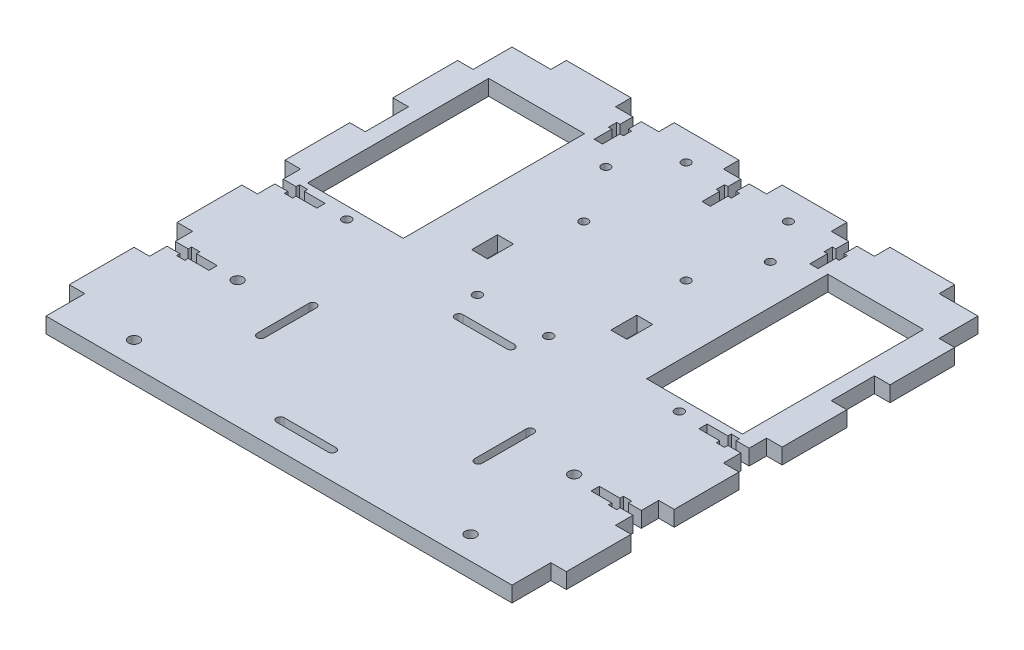
SolidWorks part; units mm, degrees
material "Oak"
ref_plane "Front Plane" through (0, 0, 0) normal (0, 0, 1) x (1, 0, 0)
ref_plane "Top Plane" through (0, 0, 0) normal (0, 1, 0) x (1, 0, 0)
ref_plane "Right Plane" through (0, 0, 0) normal (1, 0, 0) x (0, 0, -1)
sketch "Sketch1" plane through (0, 0, 0) normal (0, 1, 0) x (1, 0, 0)
  line L0 (0, -3.3) -> (0, 3.3) construction
  line L1 (-90, -90) -> (90, -90)
  line L2 (-90, -90) -> (-90, -75)
  line L3 (-90, 90) -> (-75, 90)
  line L4 (90, -90) -> (90, -75)
  line L5 (-90, -90) -> (90, 90) construction
  line L6 (-90, 90) -> (90, -90) construction
  line L7 (23.8, 24.4) -> (30, 24.4)
  line L8 (23.8, 24.4) -> (23.8, 14.4)
  line L9 (23.8, 14.4) -> (30, 14.4)
  line L10 (30, 24.4) -> (30, 14.4)
  line L11 (47, 75) -> (84, 75)
  line L12 (47, 75) -> (47, 5)
  line L13 (47, 5) -> (84, 5)
  line L14 (84, 75) -> (84, 5)
  line L15 (-47, 5) -> (-84, 5)
  line L16 (-84, 75) -> (-84, 5)
  line L17 (-47, 75) -> (-84, 75)
  line L18 (-47, 75) -> (-47, 5)
  line L19 (-23.8, 14.4) -> (-30, 14.4)
  line L20 (-30, 24.4) -> (-30, 14.4)
  line L21 (-23.8, 24.4) -> (-30, 24.4)
  line L22 (-23.8, 24.4) -> (-23.8, 14.4)
  line L24 (30, 19.4) -> (47, 19.4) construction
  line L25 (-90, 75) -> (-96, 75)
  line L27 (-90, 50) -> (-96, 50)
  line L28 (-96, 75) -> (-96, 50)
  line L29 (-90, 33.3333) -> (-96, 33.3333)
  line L30 (-96, 33.3333) -> (-96, 8.3333)
  line L31 (-90, 8.3333) -> (-96, 8.3333)
  line L33 (-90, -8.3333) -> (-96, -8.3333)
  line L34 (-96, -8.3333) -> (-96, -33.3333)
  line L35 (-90, -33.3333) -> (-96, -33.3333)
  line L37 (-90, -50) -> (-96, -50)
  line L38 (-96, -50) -> (-96, -75)
  line L39 (-90, -75) -> (-96, -75)
  line L40 (-90, 33.3333) -> (-90, 50)
  line L41 (-90, 1.6) -> (-85, 1.6)
  line L43 (-90, -1.6) -> (-85, -1.6)
  line L44 (-73.8, 1.6) -> (-73.8, -1.6)
  line L45 (-85, 2.9) -> (-81.8, 2.9)
  line L46 (-85, 2.9) -> (-85, 1.6)
  line L47 (-85, -2.9) -> (-81.8, -2.9)
  line L48 (-81.8, 2.9) -> (-81.8, 1.6)
  line L49 (-42, -35) -> (-42, -55) construction
  line L50 (-90, 75) -> (-90, 90)
  line L51 (-90, -8.3333) -> (-90, -1.6)
  line L52 (-90, -50) -> (-90, -43.2667)
  line L53 (-85, -1.6) -> (-85, -2.9)
  line L54 (-81.8, -1.6) -> (-73.8, -1.6)
  line L55 (-81.8, 1.6) -> (-73.8, 1.6)
  line L56 (-81.8, -1.6) -> (-81.8, -2.9)
  line L57 (-90, 1.6) -> (-90, 8.3333)
  line L58 (-90, -40.0667) -> (-85, -40.0667)
  line L59 (-90, -43.2667) -> (-85, -43.2667)
  line L60 (-73.8, -40.0667) -> (-73.8, -43.2667)
  line L61 (-85, -38.7667) -> (-81.8, -38.7667)
  line L62 (-85, -38.7667) -> (-85, -40.0667)
  line L63 (-85, -44.5667) -> (-81.8, -44.5667)
  line L64 (-81.8, -38.7667) -> (-81.8, -40.0667)
  line L65 (-85, -43.2667) -> (-85, -44.5667)
  line L66 (-81.8, -43.2667) -> (-73.8, -43.2667)
  line L67 (-81.8, -40.0667) -> (-73.8, -40.0667)
  line L68 (-81.8, -43.2667) -> (-81.8, -44.5667)
  line L69 (-90, -40.0667) -> (-90, -33.3333)
  line L70 (90, -75) -> (96, -75)
  line L71 (81.8, -38.7667) -> (81.8, -40.0667)
  line L72 (85, -38.7667) -> (81.8, -38.7667)
  line L73 (85, -38.7667) -> (85, -40.0667)
  line L74 (81.8, -43.2667) -> (81.8, -44.5667)
  line L75 (81.8, -40.0667) -> (73.8, -40.0667)
  line L76 (81.8, -43.2667) -> (73.8, -43.2667)
  line L77 (85, -43.2667) -> (85, -44.5667)
  line L78 (85, -44.5667) -> (81.8, -44.5667)
  line L79 (73.8, -40.0667) -> (73.8, -43.2667)
  line L80 (90, -43.2667) -> (85, -43.2667)
  line L81 (90, -40.0667) -> (85, -40.0667)
  line L82 (96, -50) -> (96, -75)
  line L83 (90, -50) -> (96, -50)
  line L84 (90, -33.3333) -> (96, -33.3333)
  line L85 (90, -8.3333) -> (96, -8.3333)
  line L86 (96, -8.3333) -> (96, -33.3333)
  line L87 (81.8, -1.6) -> (81.8, -2.9)
  line L88 (81.8, 1.6) -> (73.8, 1.6)
  line L89 (81.8, -1.6) -> (73.8, -1.6)
  line L90 (85, -1.6) -> (85, -2.9)
  line L91 (81.8, 2.9) -> (81.8, 1.6)
  line L92 (85, -2.9) -> (81.8, -2.9)
  line L93 (85, 2.9) -> (85, 1.6)
  line L94 (85, 2.9) -> (81.8, 2.9)
  line L95 (73.8, 1.6) -> (73.8, -1.6)
  line L96 (90, -1.6) -> (85, -1.6)
  line L97 (90, 1.6) -> (85, 1.6)
  line L98 (90, 8.3333) -> (96, 8.3333)
  line L99 (96, 33.3333) -> (96, 8.3333)
  line L100 (90, 33.3333) -> (96, 33.3333)
  line L101 (90, 50) -> (96, 50)
  line L102 (96, 75) -> (96, 50)
  line L103 (90, 75) -> (96, 75)
  line L104 (90, 75) -> (90, 90)
  line L105 (90, 33.3333) -> (90, 50)
  line L106 (90, 1.6) -> (90, 8.3333)
  line L107 (90, -8.3333) -> (90, -1.6)
  line L108 (90, -50) -> (90, -43.2667)
  line L109 (90, -40.0667) -> (90, -33.3333)
  line L110 (-33.3333, 90) -> (-33.3333, 96)
  line L112 (-75, 90) -> (-75, 96)
  line L113 (-75, 96) -> (-50, 96)
  line L114 (-50, 90) -> (-50, 96)
  line L116 (-8.3333, 90) -> (-8.3333, 96)
  line L117 (-33.3333, 96) -> (-8.3333, 96)
  line L118 (8.3333, 90) -> (8.3333, 96)
  line L120 (33.3333, 90) -> (33.3333, 96)
  line L121 (8.3333, 96) -> (33.3333, 96)
  line L122 (50, 90) -> (50, 96)
  line L124 (75, 90) -> (75, 96)
  line L125 (50, 96) -> (75, 96)
  line L126 (-40.0667, 90) -> (-33.3333, 90)
  line L128 (-43.2667, 90) -> (-43.2667, 85)
  line L129 (-43.2667, 75) -> (-40.0667, 75)
  line L130 (-40.0667, 90) -> (-40.0667, 85)
  line L131 (-50, 90) -> (-43.2667, 90)
  line L132 (-8.3333, 90) -> (-1.6, 90)
  line L133 (-40.0667, 85) -> (-38.7667, 85)
  line L134 (-44.5667, 85) -> (-43.2667, 85)
  line L135 (-44.5667, 85) -> (-44.5667, 81.8)
  line L136 (-44.5667, 81.8) -> (-43.2667, 81.8)
  line L137 (-38.7667, 85) -> (-38.7667, 81.8)
  line L138 (-43.2667, 81.8) -> (-43.2667, 75)
  line L139 (-40.0667, 81.8) -> (-38.7667, 81.8)
  line L140 (-40.0667, 81.8) -> (-40.0667, 75)
  line L141 (-1.6, 90) -> (-1.6, 85)
  line L142 (-1.6, 75) -> (1.6, 75)
  line L143 (1.6, 90) -> (1.6, 85)
  line L144 (1.6, 85) -> (2.9, 85)
  line L145 (-2.9, 85) -> (-1.6, 85)
  line L146 (-2.9, 85) -> (-2.9, 81.8)
  line L147 (-2.9, 81.8) -> (-1.6, 81.8)
  line L148 (2.9, 85) -> (2.9, 81.8)
  line L149 (-1.6, 81.8) -> (-1.6, 75)
  line L150 (1.6, 81.8) -> (2.9, 81.8)
  line L151 (1.6, 81.8) -> (1.6, 75)
  line L152 (40.0667, 90) -> (40.0667, 85)
  line L153 (40.0667, 75) -> (43.2667, 75)
  line L154 (43.2667, 90) -> (43.2667, 85)
  line L155 (43.2667, 85) -> (44.5667, 85)
  line L156 (38.7667, 85) -> (40.0667, 85)
  line L157 (38.7667, 85) -> (38.7667, 81.8)
  line L158 (38.7667, 81.8) -> (40.0667, 81.8)
  line L159 (44.5667, 85) -> (44.5667, 81.8)
  line L160 (40.0667, 81.8) -> (40.0667, 75)
  line L161 (43.2667, 81.8) -> (44.5667, 81.8)
  line L162 (43.2667, 81.8) -> (43.2667, 75)
  line L163 (1.6, 90) -> (8.3333, 90)
  line L164 (43.2667, 90) -> (50, 90)
  line L165 (33.3333, 90) -> (40.0667, 90)
  line L166 (75, 90) -> (90, 90)
  line L167 (-40.5, -35) -> (-40.5, -55)
  line L168 (-43.5, -35) -> (-43.5, -55)
  line L169 (-90, -75) -> (-90, -50) construction
  line L170 (42, -35) -> (42, -55) construction
  line L171 (40.5, -35) -> (40.5, -55)
  line L172 (43.5, -35) -> (43.5, -55)
  line L173 (10, -10.5) -> (-10, -10.5) construction
  line L174 (10, -12) -> (-10, -12)
  line L175 (10, -9) -> (-10, -9)
  line L176 (-42, -45) -> (42, -45) construction
  line L177 (10, -79.5) -> (-10, -79.5) construction
  line L178 (10, -78) -> (-10, -78)
  line L179 (10, -81) -> (-10, -81)
  circle A0 centre (65, -41) radius 2.1
  circle A1 centre (65, -81) radius 2.1
  circle A3 centre (-65, -81) radius 2.1
  circle A5 centre (-65, -41) radius 2.1
  circle A6 centre (13.7704, 0.4) radius 1.6 construction
  circle A7 centre (-13.7704, 0.4) radius 1.6 construction
  circle A16 centre (31.75, 68) radius 1.5 construction
  circle A17 centre (-31.75, 68) radius 1.5 construction
  circle A18 centre (31.75, 68) radius 1.5 construction
  circle A19 centre (-31.75, 68) radius 1.5 construction
  circle A24 centre (21.75, 45.5) radius 1.65
  circle A25 centre (-17.75, 45.5) radius 1.65
  circle A26 centre (-17.75, 85) radius 1.65
  circle A27 centre (21.75, 85) radius 1.65
  circle A28 centre (-31.75, 68) radius 1.65
  circle A29 centre (31.75, 68) radius 1.65
  circle A32 centre (13.7704, 0.4) radius 1.6 construction
  circle A33 centre (-13.7704, 0.4) radius 1.6 construction
  circle A34 centre (-13.7704, 0.4) radius 1.7
  circle A35 centre (13.7704, 0.4) radius 1.7
  circle A36 centre (64.2296, 0.4) radius 1.6 construction
  circle A37 centre (-64.2296, 0.4) radius 1.6 construction
  circle A38 centre (64.2296, 0.4) radius 1.6 construction
  circle A39 centre (-64.2296, 0.4) radius 1.6 construction
  circle A40 centre (64.2296, 0.4) radius 1.7
  circle A41 centre (-64.2296, 0.4) radius 1.7
  arc A42 (-40.5, -35) -> (-43.5, -35) centre (-42, -35) ccw
  arc A43 (-43.5, -55) -> (-40.5, -55) centre (-42, -55) ccw
  arc A44 (40.5, -35) -> (43.5, -35) centre (42, -35) cw
  arc A45 (43.5, -55) -> (40.5, -55) centre (42, -55) cw
  arc A46 (10, -12) -> (10, -9) centre (10, -10.5) ccw
  arc A47 (-10, -9) -> (-10, -12) centre (-10, -10.5) ccw
  arc A48 (10, -78) -> (10, -81) centre (10, -79.5) cw
  arc A49 (-10, -81) -> (-10, -78) centre (-10, -79.5) cw
  point P0 (0, 0)
  point P15 (30, 19.4)
  point P17 (47, 40)
  point P208 (-42, -45)
  point P217 (42, -45)
  point P224 (0, -10.5)
  point P233 (0, -79.5)
  dimension "D11" = 4.2
  dimension "D13" = 40
  dimension "D14" = 9
  dimension "D15" = 25
  dimension "D16" = 25
  dimension "D18" = 3.3
  dimension "D20" = 5
  dimension "D21" = 25.25
  dimension "D2" = 39.5
  dimension "D19" = 39.5
  dimension "D1" = 180
  dimension "D3" = 10
  dimension "D4" = 6.2
  dimension "D5" = 37
  dimension "D6" = 70
  dimension "D7" = 6
  dimension "D8" = 15
  dimension "D9" = 17
  dimension "D10" = 20.6
  dimension "D22" = 6
  dimension "D23" = 15
  dimension "D25" = 15
  dimension "D26" = 180
  dimension "D27" = 3.2
  dimension "D28" = 3.2
  dimension "D29" = 5.8
  dimension "D30" = 5
  dimension "D31" = 8
  dimension "D32" = 2
  dimension "D33" = 25
  dimension "D34" = 15
  dimension "D35" = 6
  dimension "D37" = 15
  dimension "D38" = 3.2
  dimension "D39" = 15
  dimension "D40" = 3.2
  dimension "D41" = 5.8
  dimension "D42" = 5
  dimension "D46" = 3
  dimension "D47" = 20
  dimension "D48" = 45
  dimension "D49" = 48
  dimension "D50" = 20
  dimension "D51" = 33
  dimension "D52" = 3
  dimension "D53" = 33
  dimension "D17" = 0.15
  dimension "D44" = 0.1
  dimension "D45" = 0.1
  dimension "D12" = 2
  dimension "D24" = 4
  dimension "D36" = 4
  dimension "D43" = 3
extrude "Boss-Extrude1" add sketch "Sketch1" along normal blind 6
sketch "Sketch2" plane through (0, 6, 0) normal (0, 1, 0) x (1, 0, 0)
sketch_block_instance "Block1-1"
sketch_block "Block1"
